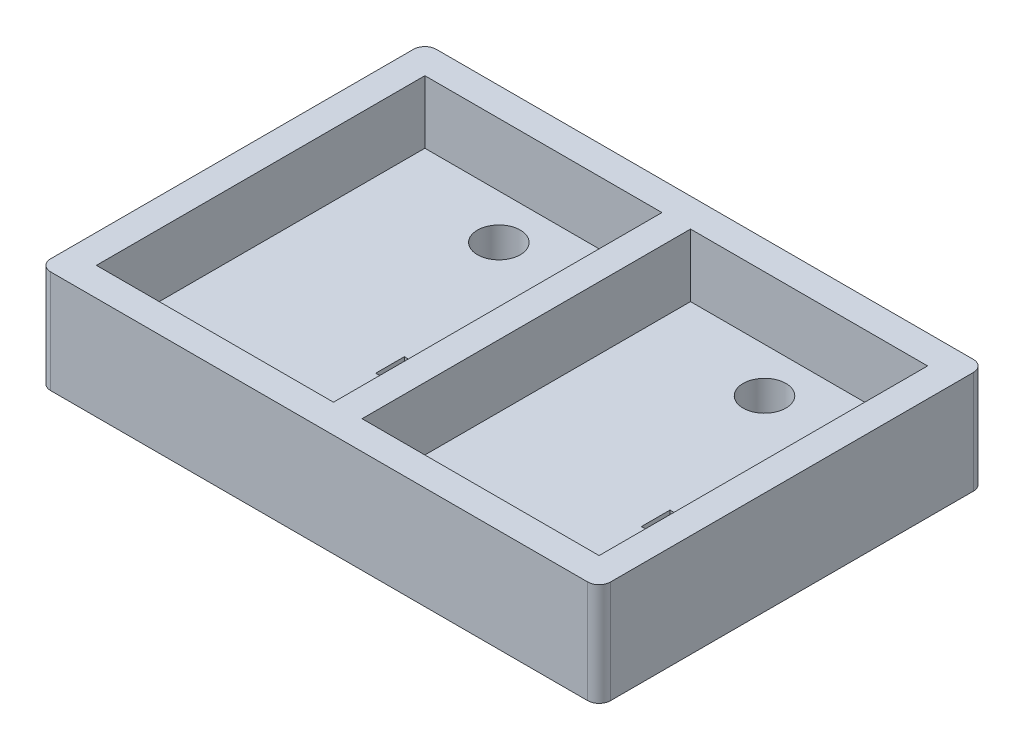
SolidWorks part; units mm, degrees
material "ABS"
ref_plane "Front Plane" through (0, 0, 0) normal (0, 0, 1) x (1, 0, 0)
ref_plane "Top Plane" through (0, 0, 0) normal (0, 1, 0) x (1, 0, 0)
ref_plane "Right Plane" through (0, 0, 0) normal (1, 0, 0) x (0, 0, -1)
sketch "Sketch1" plane through (0, 0, 0) normal (0, 1, 0) x (1, 0, 0)
  line L1 (0, 0) -> (65.405, 0)
  line L2 (0, 0) -> (0, 85.725)
  line L3 (0, 85.725) -> (65.405, 85.725)
  line L4 (65.405, 0) -> (65.405, 85.725)
  dimension "D1" = 85.725
  dimension "D2" = 65.405
extrude "Boss-Extrude1" add sketch "Sketch1" along normal blind 22.86
sketch "Sketch2" plane through (0, 22.86, 0) normal (0, 1, 0) x (1, 0, 0)
  line L0 (32.7025, 85.725) -> (32.7025, 0) construction
  line L1 (65.405, 85.725) -> (0, 85.725) construction
  line L2 (0, 0) -> (65.405, 0) construction
  line L3 (0, 42.8625) -> (65.405, 42.8625) construction
  line L4 (0, 85.725) -> (0, 0) construction
  line L5 (65.405, 0) -> (65.405, 85.725) construction
  line L7 (6.35, 6.35) -> (59.055, 6.35)
  line L8 (6.35, 6.35) -> (6.35, 79.375)
  line L9 (6.35, 79.375) -> (59.055, 79.375)
  line L10 (59.055, 6.35) -> (59.055, 79.375)
  line L11 (6.35, 6.35) -> (59.055, 79.375) construction
  line L12 (6.35, 79.375) -> (59.055, 6.35) construction
  point P12 (32.7025, 42.8625)
  dimension "D1" = 6.35
  dimension "D2" = 6.35
extrude "Cut-Extrude1" cut sketch "Sketch2" against normal offset from surface (13.97 mm away) 8.89 up to face at (32.7025, 0, -42.8625)
sketch "Sketch5" plane through (0, 8.89, 0) normal (0, 1, 0) x (1, 0, 0)
  line L0 (32.7025, 79.375) -> (32.7025, 6.35) construction
  line L1 (59.055, 79.375) -> (6.35, 79.375) construction
  line L2 (6.35, 6.35) -> (59.055, 6.35) construction
  line L3 (59.055, 42.8625) -> (6.35, 42.8625) construction
  line L4 (59.055, 6.35) -> (59.055, 79.375) construction
  line L5 (6.35, 79.375) -> (6.35, 6.35) construction
  circle A0 centre (32.7025, 69.469) radius 4.7625
  dimension "D1" = 9.525
  dimension "D2" = 9.906
sketch "Sketch6" plane through (0, 8.89, 0) normal (0, 1, 0) x (1, 0, 0)
  line L0 (47.371, 16.891) -> (47.371, 10.541) construction
  line L1 (50.546, 36.957) -> (44.196, 36.957)
  line L2 (50.546, 36.957) -> (50.546, 30.607)
  line L3 (50.546, 30.607) -> (44.196, 30.607)
  line L4 (44.196, 36.957) -> (44.196, 30.607)
  line L5 (44.196, 16.891) -> (50.546, 16.891)
  line L6 (44.196, 16.891) -> (44.196, 10.541)
  line L7 (44.196, 10.541) -> (50.546, 10.541)
  line L8 (50.546, 16.891) -> (50.546, 10.541)
  line L9 (44.196, 13.716) -> (50.546, 13.716) construction
  line L11 (6.35, 6.35) -> (59.055, 6.35) construction
  line L12 (59.055, 6.35) -> (59.055, 79.375) construction
  dimension "D1" = 6.35
  dimension "D2" = 6.35
  dimension "D3" = 20.066
  dimension "D4" = 11.684
  dimension "D5" = 7.366
extrude "Cut-Extrude3" cut sketch "Sketch6" against normal blind 5.08
sketch "Sketch7" plane through (0, 3.81, 0) normal (0, 1, 0) x (1, 0, 0)
  line L0 (46.101, 13.716) -> (48.641, 13.716) construction
  line L1 (46.101, 32.512) -> (48.641, 32.512)
  line L2 (46.101, 32.512) -> (46.101, 35.052)
  line L3 (46.101, 35.052) -> (48.641, 35.052)
  line L4 (48.641, 32.512) -> (48.641, 35.052)
  line L5 (46.101, 12.446) -> (48.641, 12.446)
  line L6 (46.101, 12.446) -> (46.101, 14.986)
  line L7 (46.101, 14.986) -> (48.641, 14.986)
  line L8 (48.641, 12.446) -> (48.641, 14.986)
  line L9 (47.371, 12.446) -> (47.371, 14.986) construction
  line L10 (44.196, 16.891) -> (44.196, 10.541) construction
  line L11 (44.196, 10.541) -> (50.546, 10.541) construction
  dimension "D1" = 2.54
  dimension "D2" = 2.54
  dimension "D3" = 3.175
  dimension "D4" = 3.175
  dimension "D5" = 20.066
extrude "Cut-Extrude4" cut sketch "Sketch7" against normal through all
extrude "Cut-Extrude5" cut sketch "Sketch5" against normal through all
pattern_linear "LPattern3" count 2 spacing 59.055 along (1, 0, 0) of "Boss-Extrude1", "Cut-Extrude1", "Cut-Extrude3", "Cut-Extrude4", "Cut-Extrude5"
fillet "Fillet1" radius 2.54 4 edges at (0, 11.43, 0) (124.46, 11.43, -85.725) (124.46, 11.43, 0) (0, 11.43, -85.725)
